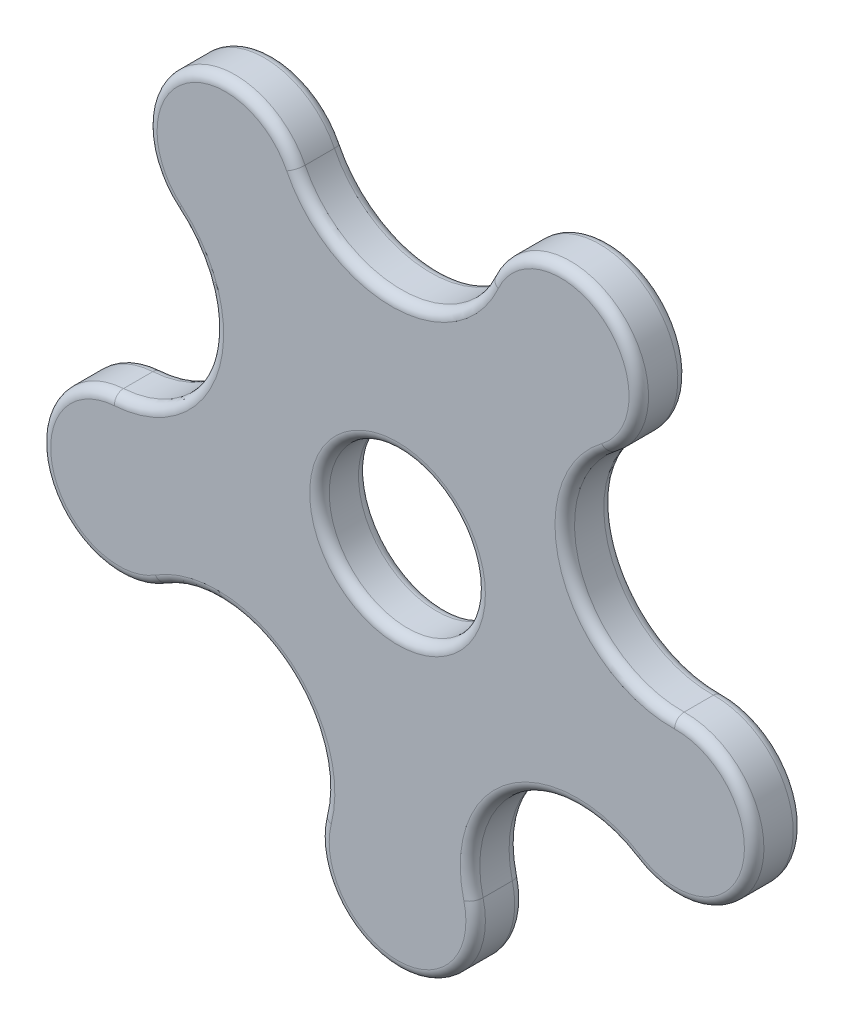
SolidWorks part; units mm, degrees
ref_plane "前视基准面" through (0, 0, 0) normal (0, 0, 1) x (1, 0, 0)
ref_plane "上视基准面" through (0, 0, 0) normal (0, 1, 0) x (1, 0, 0)
ref_plane "右视基准面" through (0, 0, 0) normal (1, 0, 0) x (0, 0, -1)
other "Configuration Table"
sketch "草图1" plane through (0, 0, 0) normal (0, 0, 1) x (1, 0, 0)
  line L0 (0, 0) -> (0, -30) construction
  line L6 (0, 0) -> (-17.6336, 24.2705) construction
  line L7 (0, 0) -> (16.712, 24.9141) construction
  line L8 (0, 0) -> (28.5317, -9.2705) construction
  line L9 (0, 0) -> (-28.5317, -9.2705) construction
  arc A1 (24.276, -16.0447) -> (28.3612, -1.2723) centre (28.5317, -9.2705) ccw
  arc A4 (-29.0706, -1.2887) -> (-24.276, -16.0447) centre (-28.5317, -9.2705) ccw
  arc A5 (-7.7577, -28.046) -> (7.7577, -28.046) centre (0, -30) ccw
  arc A6 (24.276, -16.0447) -> (7.7577, -28.046) centre (18.4245, -25.3592) ccw
  arc A7 (-7.7577, -28.046) -> (-24.276, -16.0447) centre (-18.4245, -25.3592) ccw
  arc A8 (21.5182, 18.5187) -> (28.3612, -1.2723) centre (28.1268, 9.7252) ccw
  arc A10 (-29.0706, -1.2887) -> (-22.7611, 18.1298) centre (-29.8115, 9.6863) ccw
  arc A11 (-10.467, 27.8259) -> (-22.7611, 18.1298) centre (-17.6336, 24.2705) ccw
  arc A12 (21.5182, 18.5187) -> (9.4172, 28.1984) centre (16.712, 24.9141) ccw
  arc A13 (-10.467, 27.8259) -> (9.4172, 28.1984) centre (-0.613, 32.7144) ccw
  circle A14 centre (0, 0) radius 8
  point P23 (28.3612, -1.2723)
  point P25 (28.3612, -1.2723)
  point P26 (21.7991, 18.723)
  point P27 (21.7991, 18.723)
  point P28 (12.2554, 18.2703)
  point P29 (12.2554, 18.2703)
  point P30 (-12.9313, 17.7984)
  point P31 (-12.9313, 17.7984)
  point P32 (-22.7611, 18.1298)
  point P33 (-22.7611, 18.1298)
  point P34 (-29.0706, -1.2887)
  point P35 (-29.0706, -1.2887)
  point P36 (-24.276, -16.0447)
  point P37 (-24.276, -16.0447)
  point P38 (-7.7577, -28.046)
  point P39 (-7.7577, -28.046)
  point P40 (7.7577, -28.046)
  point P41 (7.7577, -28.046)
  point P42 (24.276, -16.0447)
  point P43 (24.276, -16.0447)
  dimension "D8" = 8
  dimension "D2" = 8
  dimension "D9" = 8
  dimension "D10" = 8
  dimension "D11" = 11
  dimension "D12" = 11
  dimension "D3" = 11
  dimension "D13" = 11
  dimension "D14" = 11
  dimension "D15" = 8
  dimension "D16" = 16
  dimension "D1" = 30
  dimension "D4" = 72
  dimension "D5" = 72
  dimension "D6" = 72
  dimension "D7" = 74.147
extrude "凸台-拉伸1" add sketch "草图1" along normal blind 5
fillet "圆角1" radius 1 10 edges at (11.9589, -16.46, 5) (0, -38, 5) (-11.9589, -16.46, 5) (-36.1401, -11.7426, 5) (-19.3499, 6.2872, 5) (-22.5876, 30.552, 5) (-0.4069, 21.7164, 5) (21.7092, 31.1613, 5) (17.7307, 6.1306, 5) (36.2423, -11.4028, 5)
fillet "圆角2" radius 1 10 edges at (36.2423, -11.4028, 0) (11.9589, -16.46, 0) (0, -38, 0) (-11.9589, -16.46, 0) (-36.1401, -11.7426, 0) (-19.3499, 6.2872, 0) (-22.5876, 30.552, 0) (-0.4069, 21.7164, 0) (21.7092, 31.1613, 0) (17.7307, 6.1306, 0)
fillet "圆角3" radius 1 1 edges at (8, 0, 5)
fillet "圆角4" radius 1 1 edges at (8, 0, 0)
